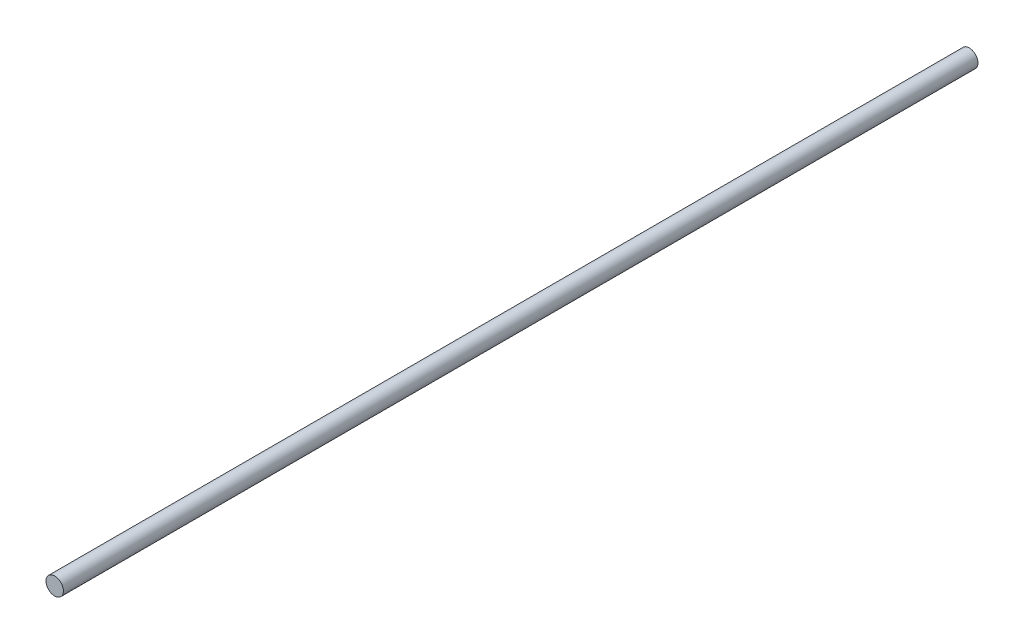
SolidWorks part; units mm, degrees
ref_plane "Спереди" through (0, 0, 0) normal (0, 0, 1) x (1, 0, 0)
ref_plane "Сверху" through (0, 0, 0) normal (0, 1, 0) x (1, 0, 0)
ref_plane "Справа" through (0, 0, 0) normal (1, 0, 0) x (0, 0, -1)
sketch "Эскиз1" plane through (0, 0, 0) normal (0, 0, 1) x (1, 0, 0)
  circle A0 centre (0, 0) radius 4
  dimension "D1" = 8
extrude "Бобышка-Вытянуть1" add sketch "Эскиз1" along normal blind 420
